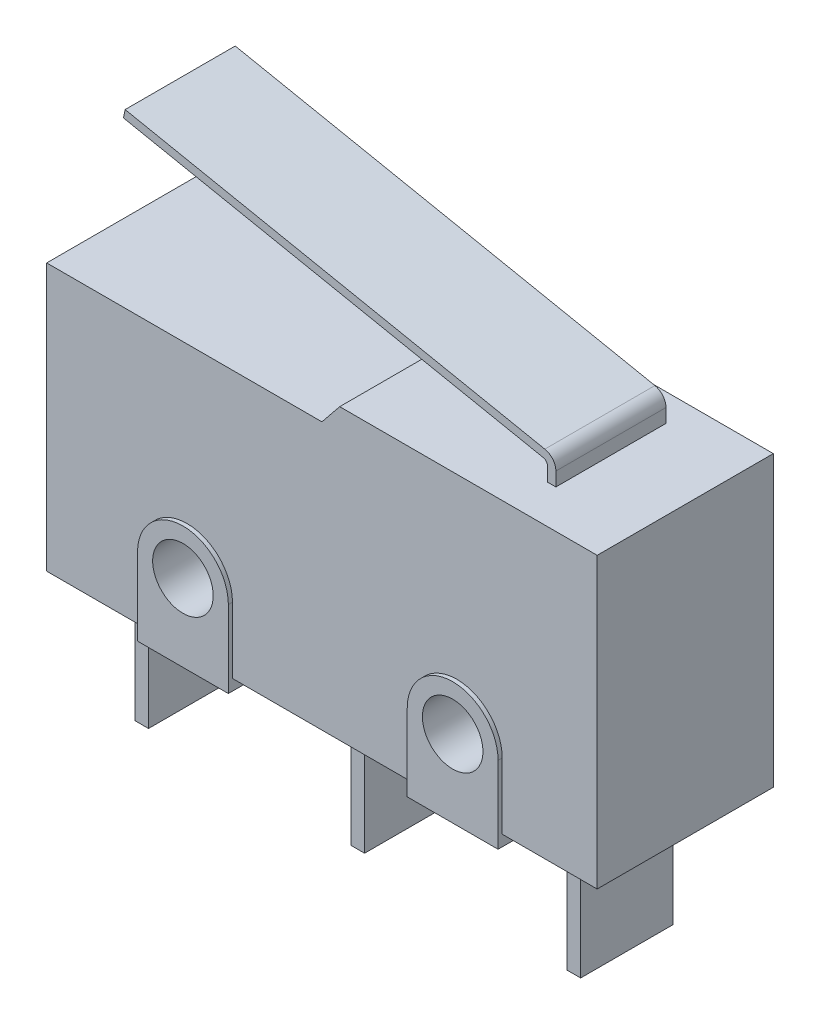
SolidWorks part; units mm, degrees
ref_plane "Front Plane" through (0, 0, 0) normal (0, 0, 1) x (1, 0, 0)
ref_plane "Top Plane" through (0, 0, 0) normal (0, 1, 0) x (1, 0, 0)
ref_plane "Right Plane" through (0, 0, 0) normal (1, 0, 0) x (0, 0, -1)
sketch "Sketch1" plane through (0, 0, 0) normal (0, 0, 1) x (1, 0, 0)
  line L0 (-10, 4.85) -> (0, 4.85)
  line L1 (-10, 4.85) -> (10, 4.85) construction
  line L2 (-10, 4.85) -> (-10, -4.85)
  line L3 (-10, -4.85) -> (10, -4.85)
  line L4 (10, 4.85) -> (10, -4.85)
  line L5 (-10, 4.85) -> (10, -4.85) construction
  line L6 (-10, -4.85) -> (10, 4.85) construction
  line L7 (0, 4.85) -> (0.646, 5.65)
  line L8 (0.646, 5.65) -> (10, 5.65)
  line L9 (10, 5.65) -> (10, 4.85)
  point P0 (0, 0)
  dimension "D1" = 20
  dimension "D2" = 9.7
  dimension "D3" = 10.5
extrude "Boss-Extrude1" add sketch "Sketch1" along normal blind 6.4
sketch "Sketch3" plane through (0, 0, 6.4) normal (0, 0, 1) x (1, 0, 0)
  line L0 (-6, 4.85) -> (-6, -4.85) construction
  line L1 (-10, -4.85) -> (10, -4.85) construction
  line L2 (0, 4.85) -> (-10, 4.85) construction
  line L3 (-10, 4.85) -> (-10, -4.85) construction
  line L4 (-10, -1.35) -> (10, -1.35) construction
  line L5 (10, -4.85) -> (10, 5.65) construction
  circle A0 centre (-4.9, -2.45) radius 1.1
  dimension "D2" = 2.2
  dimension "D1" = 4
  dimension "D3" = 6.2
extrude "Cut-Extrude1" cut sketch "Sketch3" against normal through all
sketch "Sketch4" plane through (0, 0, 6.4) normal (0, 0, 1) x (1, 0, 0)
  line L0 (-6.55, -2.45) -> (-6.55, -5.25)
  line L1 (-6.55, -5.25) -> (-3.25, -5.25)
  line L2 (-3.25, -5.25) -> (-3.25, -2.45)
  line L3 (0, 4.85) -> (-10, 4.85) construction
  arc A0 (-3.25, -2.45) -> (-6.55, -2.45) centre (-4.9, -2.45) ccw
  circle A2 centre (-4.9, -2.45) radius 1.1 construction
  circle A3 centre (-4.9, -2.45) radius 1.1
  dimension "D1" = 3.3
  dimension "D2" = 10.1
extrude "Boss-Extrude2" add sketch "Sketch4" along normal blind 0.15 and the other way blind 6.55
sketch "Sketch5" plane through (0, -4.85, 0) normal (0, -1, 0) x (1, 0, 0)
  line L0 (-10, 6.4) -> (-6.55, 6.4) construction
  line L1 (-8.1, 1.75) -> (-7.6, 1.75)
  line L2 (-8.1, 1.75) -> (-8.1, 5.1)
  line L3 (-8.1, 5.1) -> (-7.6, 5.1)
  line L4 (-7.6, 1.75) -> (-7.6, 5.1)
  line L5 (-8.1, 1.75) -> (-7.6, 5.1) construction
  line L6 (-8.1, 5.1) -> (-7.6, 1.75) construction
  line L7 (-10, 0) -> (-6.55, 0) construction
  line L8 (-10, 6.4) -> (-10, 0) construction
  point P0 (-7.85, 3.425)
  point P7 (-8.275, 0)
  dimension "D1" = 1.3
  dimension "D2" = 1.75
  dimension "D3" = 0.5
  dimension "D4" = 1.9
extrude "Boss-Extrude3" add sketch "Sketch5" along normal blind 4.4
sketch "Sketch6" plane through (0, -4.85, -4.85) normal (0, 1, 0) x (-1, 0, 0)
  line L0 (8.1, 6.6) -> (7.6, 6.6) construction
  line L1 (-0.25, 6.6) -> (0.25, 6.6)
  line L2 (-0.25, 6.6) -> (-0.25, 9.95)
  line L3 (-0.25, 9.95) -> (0.25, 9.95)
  line L4 (0.25, 6.6) -> (0.25, 9.95)
  line L5 (-0.25, 6.6) -> (0.25, 9.95) construction
  line L6 (-0.25, 9.95) -> (0.25, 6.6) construction
  line L8 (0, 9.95) -> (0, 11.25) construction
  line L9 (7.6, 9.95) -> (8.1, 9.95) construction
  line L10 (10, 11.25) -> (-10, 11.25) construction
  point P0 (0, 8.275)
  dimension "D3" = 0.5
extrude "Boss-Extrude4" add sketch "Sketch6" against normal up to vertex (4.4 mm away) contours L4 L3 L2 L1 up to point (-7.6, -9.25, 5.1)
mirror "Mirror1" about plane through (0, 0, 0) normal (1, 0, 0) of "Cut-Extrude1", "Boss-Extrude2", "Boss-Extrude3"
sketch "Sketch7" plane through (0, 0, 0) normal (0, 0, -1) x (-1, 0, 0)
  line L0 (-7.1, 5.65) -> (-7.1, 6.15)
  line L1 (-10, 5.65) -> (-0.646, 5.65) construction
  line L2 (-6.6984, 6.6402) -> (8.55, 9.7)
  line L3 (0, 4.85) -> (10, 4.85) construction
  line L4 (-10, -4.85) -> (-10, 5.65) construction
  line L5 (10, 4.85) -> (10, -4.85) construction
  arc A0 (-7.1, 6.15) -> (-6.6984, 6.6402) centre (-6.6, 6.15) cw
  dimension "D2" = 0.5
  dimension "D1" = 4.85
  dimension "D3" = 0.5
  dimension "D4" = 2.9
  dimension "D5" = 1.45
extrude "Extrude-Thin2" add sketch "Sketch7" against normal blind 4 from offset 1 thin offset against normal yes
